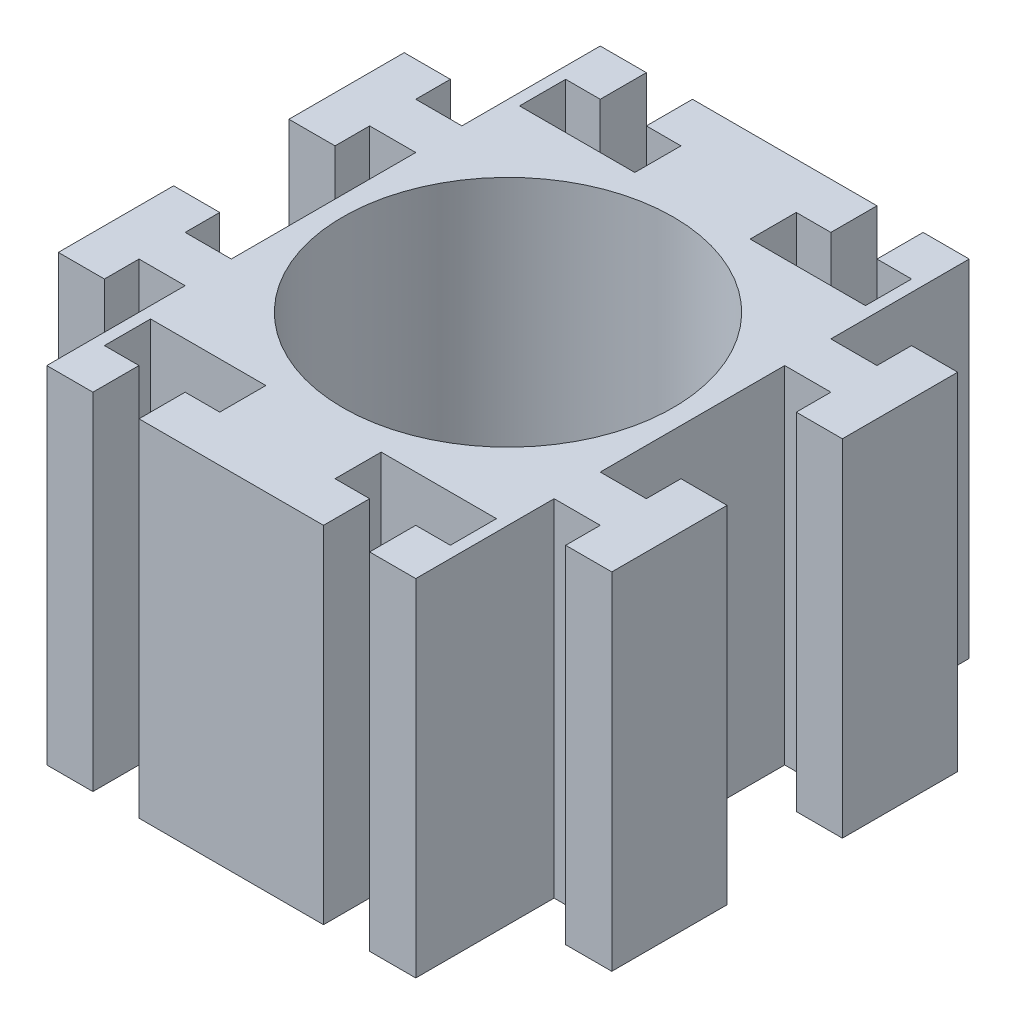
SolidWorks part; units mm, degrees
ref_plane "Front Plane" through (0, 0, 0) normal (0, 0, 1) x (1, 0, 0)
ref_plane "Top Plane" through (0, 0, 0) normal (0, 1, 0) x (1, 0, 0)
ref_plane "Right Plane" through (0, 0, 0) normal (1, 0, 0) x (0, 0, -1)
sketch "Sketch1" plane through (0, 0, 0) normal (0, 1, 0) x (1, 0, 0)
  line L1 (-15.24, -15.24) -> (15.24, -15.24)
  line L2 (-15.24, -15.24) -> (-15.24, 15.24)
  line L3 (-15.24, 15.24) -> (15.24, 15.24)
  line L4 (15.24, -15.24) -> (15.24, 15.24)
  line L5 (-15.24, -15.24) -> (15.24, 15.24) construction
  line L6 (-15.24, 15.24) -> (15.24, -15.24) construction
  point P0 (0, 0)
  point P6 (10.5171, -9)
  dimension "D1" = 30.48
extrude "Boss-Extrude1" add sketch "Sketch1" along normal blind 19.05
sketch "Sketch4" plane through (0, 19.05, 0) normal (0, 1, 0) x (1, 0, 0)
  circle A0 centre (0, 0) radius 9.1
  dimension "D1" = 18.2
extrude "Cut-Extrude1" cut sketch "Sketch4" against normal blind 15.24
sketch "Sketch5" plane through (0, 0, 0) normal (0, -1, 0) x (1, 0, 0)
  circle A0 centre (0, 0) radius 2.67
extrude "Cut-Extrude2" cut sketch "Sketch5" against normal up to next
sketch "Sketch6" plane through (0, 19.05, 0) normal (0, 1, 0) x (1, 0, 0)
  line L0 (-7.62, 15.24) -> (-7.62, 12.7)
  line L1 (15.24, -15.24) -> (15.24, 15.24) construction
  line L2 (15.24, 15.24) -> (-15.24, 15.24) construction
  line L3 (-7.62, 12.7) -> (-9.525, 12.7)
  line L4 (-9.525, 12.7) -> (-9.525, 10.16)
  line L5 (-9.525, 10.16) -> (-3.175, 10.16)
  line L6 (-3.175, 10.16) -> (-3.175, 12.7)
  line L7 (-3.175, 12.7) -> (-5.08, 12.7)
  line L8 (-5.08, 12.7) -> (-5.08, 15.24)
  line L9 (-5.08, 15.24) -> (5.08, 15.24)
  line L10 (5.08, 15.24) -> (5.08, 12.7)
  line L11 (5.08, 12.7) -> (3.175, 12.7)
  line L12 (3.175, 12.7) -> (3.175, 10.16)
  line L13 (3.175, 10.16) -> (9.525, 10.16)
  line L14 (9.525, 10.16) -> (9.525, 12.7)
  line L15 (9.525, 12.7) -> (7.62, 12.7)
  line L16 (7.62, 12.7) -> (7.62, 15.24)
  line L17 (7.62, 15.24) -> (10.16, 15.24)
  line L18 (0, 0) -> (-15.24, 0) construction
  line L19 (-7.62, 15.24) -> (-10.16, 15.24)
  line L20 (0, 0) -> (0, 15.24) construction
  line L21 (10.16, 15.24) -> (10.16, 7.62)
  line L22 (10.16, 7.62) -> (12.7, 7.62)
  line L23 (12.7, 7.62) -> (12.7, 9.525)
  line L24 (12.7, 9.525) -> (15.24, 9.525)
  line L25 (15.24, 9.525) -> (15.24, 3.175)
  line L26 (15.24, 3.175) -> (12.7, 3.175)
  line L27 (12.7, 3.175) -> (12.7, 5.08)
  line L28 (12.7, 5.08) -> (10.16, 5.08)
  line L29 (10.16, 5.08) -> (10.16, -5.08)
  line L30 (10.16, -5.08) -> (12.7, -5.08)
  line L31 (12.7, -5.08) -> (12.7, -3.175)
  line L32 (12.7, -3.175) -> (15.24, -3.175)
  line L33 (15.24, -3.175) -> (15.24, -9.525)
  line L34 (15.24, -9.525) -> (12.7, -9.525)
  line L35 (12.7, -9.525) -> (12.7, -7.62)
  line L36 (12.7, -7.62) -> (10.16, -7.62)
  line L37 (10.16, -7.62) -> (10.16, -15.24)
  line L38 (-15.24, -15.24) -> (15.24, -15.24) construction
  line L39 (10.16, -15.24) -> (7.62, -15.24)
  line L40 (7.62, -15.24) -> (7.62, -12.7)
  line L41 (7.62, -12.7) -> (9.525, -12.7)
  line L42 (9.525, -12.7) -> (9.525, -10.16)
  line L43 (9.525, -10.16) -> (3.175, -10.16)
  line L44 (3.175, -10.16) -> (3.175, -12.7)
  line L45 (3.175, -12.7) -> (5.08, -12.7)
  line L46 (5.08, -12.7) -> (5.08, -15.24)
  line L47 (5.08, -15.24) -> (-5.08, -15.24)
  line L48 (-5.08, -15.24) -> (-5.08, -12.7)
  line L49 (-5.08, -12.7) -> (-3.175, -12.7)
  line L50 (-3.175, -12.7) -> (-3.175, -10.16)
  line L51 (-3.175, -10.16) -> (-9.525, -10.16)
  line L52 (-9.525, -10.16) -> (-9.525, -12.7)
  line L53 (-9.525, -12.7) -> (-7.62, -12.7)
  line L54 (-7.62, -12.7) -> (-7.62, -15.24)
  line L55 (-7.62, -15.24) -> (-10.16, -15.24)
  line L56 (-10.16, -15.24) -> (-10.16, -7.62)
  line L57 (-10.16, -7.62) -> (-12.7, -7.62)
  line L58 (-12.7, -7.62) -> (-12.7, -9.525)
  line L59 (-12.7, -9.525) -> (-15.24, -9.525)
  line L60 (-15.24, 15.24) -> (-15.24, -15.24) construction
  line L61 (-15.24, -9.525) -> (-15.24, -3.175)
  line L62 (-15.24, -3.175) -> (-12.7, -3.175)
  line L63 (-12.7, -3.175) -> (-12.7, -5.08)
  line L64 (-12.7, -5.08) -> (-10.16, -5.08)
  line L65 (-10.16, -5.08) -> (-10.16, 5.08)
  line L66 (-10.16, 5.08) -> (-12.7, 5.08)
  line L67 (-12.7, 5.08) -> (-12.7, 3.175)
  line L68 (-12.7, 3.175) -> (-15.24, 3.175)
  line L69 (-15.24, 3.175) -> (-15.24, 9.525)
  line L70 (-15.24, 9.525) -> (-12.7, 9.525)
  line L71 (-12.7, 9.525) -> (-12.7, 7.62)
  line L72 (-12.7, 7.62) -> (-10.16, 7.62)
  line L73 (-10.16, 15.24) -> (-10.16, 7.62)
  point P15 (5.3658, -12.2126)
  point P80 (12.7, -8.7004)
  dimension "D1" = 6.35
  dimension "D2" = 2.54
  dimension "D3" = 6.35
  dimension "D4" = 2.54
  dimension "D5" = 2.54
  dimension "D6" = 5.08
  dimension "D7" = 6.35
extrude "Cut-Extrude3" cut sketch "Sketch6" against normal up to next (19.05 mm away) and the other way through all flip side to cut
